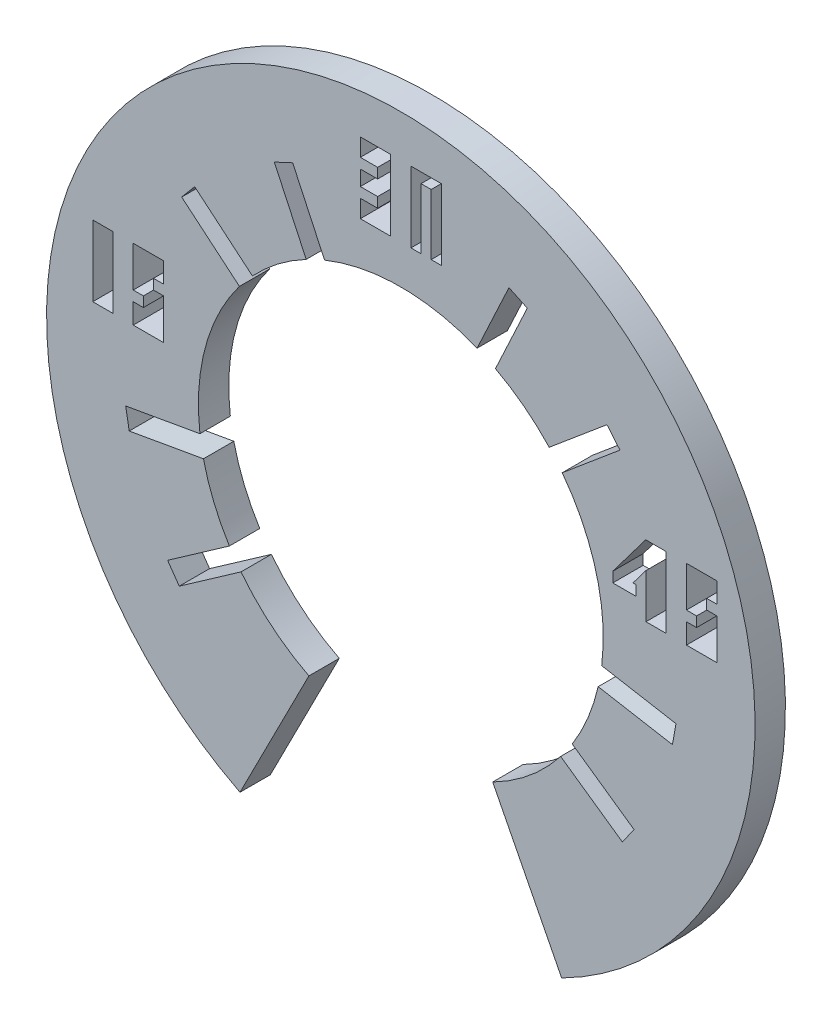
SolidWorks part; units mm, degrees
ref_plane "Спереди" through (0, 0, 0) normal (0, 0, 1) x (1, 0, 0)
ref_plane "Сверху" through (0, 0, 0) normal (0, 1, 0) x (1, 0, 0)
ref_plane "Справа" through (0, 0, 0) normal (1, 0, 0) x (0, 0, -1)
sketch "Sketch1" plane through (0, 0, 0) normal (0, 0, 1) x (1, 0, 0)
  line L1 (-4.5399, -8.9101) -> (-7.9448, -15.5926)
  line L2 (4.5399, -8.9101) -> (7.9448, -15.5926)
  arc A0 (4.5399, -8.9101) -> (-4.5399, -8.9101) centre (0, 0) ccw
  arc A1 (7.9448, -15.5926) -> (-7.9448, -15.5926) centre (0, 0) ccw
  point P34 (0, 0)
  dimension "D1" = 20
  dimension "D2" = 35
extrude "Boss-Extrude1" add sketch "Sketch1" along normal blind 1.5
sketch "Sketch2" plane through (0, 0, 1.5) normal (0, 0, 1) x (1, 0, 0)
  line L0 (0, 0) -> (0, -15.8219) construction
  line L1 (0, 0) -> (-8.75, -15.1554) construction
  line L2 (0, 0) -> (-14.3352, -10.0376) construction
  line L3 (0, 0) -> (-17.2341, -3.0388) construction
  line L4 (0, 0) -> (-16.9037, 4.5293) construction
  line L5 (0, 0) -> (-13.4058, 11.2488) construction
  line L6 (0, 0) -> (-7.3958, 15.8604) construction
  line L7 (0, 0) -> (0, 17.5) construction
  line L8 (0, 0) -> (7.3958, 15.8604) construction
  line L9 (0, 0) -> (13.4058, 11.2488) construction
  line L10 (0, 0) -> (16.9037, 4.5293) construction
  line L11 (0, 0) -> (17.2341, -3.0388) construction
  line L12 (0, 0) -> (14.3352, -10.0376) construction
  line L13 (0, 0) -> (8.75, -15.1554) construction
  line L14 (-15.218, 5.2576) -> (-14.218, 5.2576)
  line L15 (-14.218, 5.2576) -> (-14.218, 1.7576)
  line L16 (-14.218, 1.7576) -> (-15.218, 1.7576)
  line L17 (-15.218, 1.7576) -> (-15.218, 5.2576)
  line L18 (-13.218, 5.2576) -> (-13.218, 3.2576)
  line L19 (-13.218, 3.2576) -> (-12.718, 3.2576)
  line L20 (-12.718, 3.2576) -> (-12.718, 2.7576)
  line L21 (-12.718, 2.7576) -> (-13.218, 2.7576)
  line L22 (-13.218, 2.7576) -> (-13.218, 1.7576)
  line L23 (-13.218, 1.7576) -> (-11.718, 1.7576)
  line L24 (-11.718, 1.7576) -> (-11.718, 3.7576)
  line L25 (-11.718, 3.7576) -> (-12.218, 3.7576)
  line L26 (-12.218, 3.7576) -> (-12.218, 4.2576)
  line L27 (-12.218, 4.2576) -> (-11.718, 4.2576)
  line L28 (-11.718, 4.2576) -> (-11.718, 5.2576)
  line L29 (-11.718, 5.2576) -> (-13.218, 5.2576)
  line L30 (-2, 15.4185) -> (-0.5, 15.4185)
  line L31 (-0.5, 15.4185) -> (-0.5, 11.9185)
  line L32 (-0.5, 11.9185) -> (-2, 11.9185)
  line L33 (-2, 11.9185) -> (-2, 12.7935)
  line L34 (-2, 12.7935) -> (-1.1453, 12.7935)
  line L35 (-1.1453, 12.7935) -> (-1.1453, 13.2935)
  line L36 (-1.1453, 13.2935) -> (-2, 13.2935)
  line L37 (-2, 13.2935) -> (-2, 14.0435)
  line L38 (-2, 14.0435) -> (-1.1453, 14.0435)
  line L39 (-1.1453, 14.0435) -> (-1.1453, 14.5435)
  line L40 (-1.1453, 14.5435) -> (-2, 14.5435)
  line L41 (-2, 14.5435) -> (-2, 15.4185)
  line L42 (0.5, 15.4185) -> (0.5, 11.9185)
  line L43 (0.5, 11.9185) -> (1, 11.9185)
  line L44 (2, 11.9185) -> (2, 15.4185)
  line L45 (2, 15.4185) -> (0.5, 15.4185)
  line L46 (1, 14.9185) -> (1.5, 14.9185)
  line L47 (1.5, 14.9185) -> (1.5, 12.4185)
  line L48 (1.5, 11.9185) -> (2, 11.9185)
  line L49 (1, 12.4185) -> (1, 14.9185)
  line L50 (1, 12.4185) -> (1, 11.9185)
  line L51 (1.5, 12.4185) -> (1.5, 11.9185)
  line L52 (12.0977, 5.2314) -> (13.1104, 5.2314)
  line L53 (13.1104, 5.2314) -> (13.1104, 1.7314)
  line L54 (13.1104, 1.7314) -> (12.1104, 1.7314)
  line L55 (12.1104, 1.7314) -> (12.1104, 3.9221)
  line L56 (14.1104, 5.2314) -> (14.1104, 3.2314)
  line L57 (14.1104, 3.2314) -> (14.6104, 3.2314)
  line L58 (14.6104, 3.2314) -> (14.6104, 2.7314)
  line L59 (14.6104, 2.7314) -> (14.1104, 2.7314)
  line L60 (14.1104, 2.7314) -> (14.1104, 1.7314)
  line L61 (14.1104, 1.7314) -> (15.6104, 1.7314)
  line L62 (15.6104, 1.7314) -> (15.6104, 3.7314)
  line L63 (15.6104, 3.7314) -> (15.1104, 3.7314)
  line L64 (15.1104, 3.7314) -> (15.1104, 4.2314)
  line L65 (15.1104, 4.2314) -> (15.6104, 4.2314)
  line L66 (15.6104, 4.2314) -> (15.6104, 5.2314)
  line L67 (15.6104, 5.2314) -> (14.1104, 5.2314)
  line L68 (12.0977, 5.2314) -> (10.4706, 3.0735)
  line L69 (-11.2326, -7.8651) -> (-11.5194, -7.4556)
  line L70 (11.4706, 3.0735) -> (12.1104, 3.9221)
  line L71 (10.4706, 3.0735) -> (10.4706, 2.5723)
  line L72 (10.4706, 2.5723) -> (11.6104, 2.5723)
  line L73 (11.6104, 2.5723) -> (11.6104, 3.0735)
  line L74 (11.6104, 3.0735) -> (11.4706, 3.0735)
  line L75 (-11.5194, -7.4556) -> (-8.4681, -5.319)
  line L76 (-11.2326, -7.8651) -> (-10.9458, -8.2747)
  line L77 (-10.9458, -8.2747) -> (-7.8945, -6.1382)
  line L78 (-8.4681, -5.319) -> (-7.4734, -4.6225)
  line L79 (-7.4734, -4.6225) -> (-6.8998, -5.4417)
  line L80 (-6.8998, -5.4417) -> (-7.8945, -6.1382)
  line L81 (-13.5041, -2.3811) -> (-13.5909, -1.8887)
  line L82 (-13.5909, -1.8887) -> (-9.9226, -1.2419)
  line L83 (-13.5041, -2.3811) -> (-13.4173, -2.8735)
  line L84 (-13.4173, -2.8735) -> (-9.7489, -2.2267)
  line L85 (-9.9226, -1.2419) -> (-8.7268, -1.0311)
  line L86 (-8.7268, -1.0311) -> (-8.5531, -2.0159)
  line L87 (-8.5531, -2.0159) -> (-9.7489, -2.2267)
  line L95 (-10.5043, 8.8142) -> (-10.1829, 9.1972)
  line L96 (-10.1829, 9.1972) -> (-7.3295, 6.8029)
  line L97 (-10.5043, 8.8142) -> (-10.8257, 8.4312)
  line L98 (-10.8257, 8.4312) -> (-7.9723, 6.0368)
  line L99 (-7.3295, 6.8029) -> (-6.3993, 6.0223)
  line L100 (-6.3993, 6.0223) -> (-7.0421, 5.2563)
  line L101 (-7.0421, 5.2563) -> (-7.9723, 6.0368)
  line L102 (-5.7951, 12.4277) -> (-5.342, 12.639)
  line L103 (-5.342, 12.639) -> (-3.7677, 9.2631)
  line L104 (-5.7951, 12.4277) -> (-6.2483, 12.2164)
  line L105 (-6.2483, 12.2164) -> (-4.6741, 8.8404)
  line L106 (-3.7677, 9.2631) -> (-3.2546, 8.1626)
  line L107 (-3.2546, 8.1626) -> (-4.1609, 7.7399)
  line L108 (-4.1609, 7.7399) -> (-4.6741, 8.8404)
  line L116 (5.7951, 12.4277) -> (6.2483, 12.2164)
  line L117 (6.2483, 12.2164) -> (4.6741, 8.8404)
  line L118 (5.7951, 12.4277) -> (5.342, 12.639)
  line L119 (5.342, 12.639) -> (3.7677, 9.2631)
  line L120 (4.6741, 8.8404) -> (4.1609, 7.7399)
  line L121 (4.1609, 7.7399) -> (3.2546, 8.1626)
  line L122 (3.2546, 8.1626) -> (3.7677, 9.2631)
  line L123 (10.5043, 8.8142) -> (10.8257, 8.4312)
  line L124 (10.8257, 8.4312) -> (7.9723, 6.0368)
  line L125 (10.5043, 8.8142) -> (10.1829, 9.1972)
  line L126 (10.1829, 9.1972) -> (7.3295, 6.8029)
  line L127 (7.9723, 6.0368) -> (7.0421, 5.2563)
  line L128 (7.0421, 5.2563) -> (6.3993, 6.0223)
  line L129 (6.3993, 6.0223) -> (7.3295, 6.8029)
  line L137 (13.5041, -2.3811) -> (13.4173, -2.8735)
  line L138 (13.4173, -2.8735) -> (9.7489, -2.2267)
  line L139 (13.5041, -2.3811) -> (13.5909, -1.8887)
  line L140 (13.5909, -1.8887) -> (9.9226, -1.2419)
  line L141 (9.7489, -2.2267) -> (8.5531, -2.0159)
  line L142 (8.5531, -2.0159) -> (8.7268, -1.0311)
  line L143 (8.7268, -1.0311) -> (9.9226, -1.2419)
  line L144 (11.2326, -7.8651) -> (10.9458, -8.2747)
  line L145 (10.9458, -8.2747) -> (7.8945, -6.1382)
  line L146 (11.2326, -7.8651) -> (11.5194, -7.4556)
  line L147 (11.5194, -7.4556) -> (8.4681, -5.319)
  line L148 (7.8945, -6.1382) -> (6.8998, -5.4417)
  line L149 (6.8998, -5.4417) -> (7.4734, -4.6225)
  line L150 (7.4734, -4.6225) -> (8.4681, -5.319)
  line L165 (0, 13.7124) -> (0.5, 13.7124) [skipped]
  line L166 (0, 13.7124) -> (-0.5, 13.7124) [skipped]
  line L167 (-0.5, 13.7124) -> (-0.5, 9.9875) [skipped]
  line L168 (0.5, 13.7124) -> (0.5, 9.9875) [skipped]
  line L169 (0.5, 9.9875) -> (0.5, 8.7732) [skipped]
  line L170 (0.5, 8.7732) -> (-0.5, 8.7732) [skipped]
  line L171 (-0.5, 8.7732) -> (-0.5, 9.9875) [skipped]
  line L172 (-13.1158, 4.032) -> (-9.5178, 3.0679) [skipped]
  line L173 (-13.2452, 3.549) -> (-13.1158, 4.032) [skipped]
  line L174 (-13.2452, 3.549) -> (-13.3746, 3.0661) [skipped]
  line L175 (-13.3746, 3.0661) -> (-9.7766, 2.102) [skipped]
  line L176 (-8.6037, 1.7877) -> (-9.7766, 2.102) [skipped]
  line L177 (-9.5178, 3.0679) -> (-8.3449, 2.7536) [skipped]
  line L178 (-8.3449, 2.7536) -> (-8.6037, 1.7877) [skipped]
  line L179 (1.1951, -13.6603) -> (0.697, -13.7038) [skipped]
  line L180 (0.697, -13.7038) -> (0.3724, -9.9931) [skipped]
  line L181 (1.1951, -13.6603) -> (1.6932, -13.6167) [skipped]
  line L182 (1.6932, -13.6167) -> (1.3686, -9.9059) [skipped]
  line L183 (0.3724, -9.9931) -> (0.2665, -8.7834) [skipped]
  line L184 (0.2665, -8.7834) -> (1.2627, -8.6963) [skipped]
  line L185 (1.2627, -8.6963) -> (1.3686, -9.9059) [skipped]
  line L186 (13.1158, 4.032) -> (9.5178, 3.0679) [skipped]
  line L187 (13.3746, 3.0661) -> (9.7766, 2.102) [skipped]
  line L188 (13.2452, 3.549) -> (13.1158, 4.032) [skipped]
  line L189 (13.2452, 3.549) -> (13.3746, 3.0661) [skipped]
  line L190 (8.3449, 2.7536) -> (9.5178, 3.0679) [skipped]
  line L191 (9.7766, 2.102) -> (8.6037, 1.7877) [skipped]
  line L192 (8.6037, 1.7877) -> (8.3449, 2.7536) [skipped]
  line L193 (4.5607, -8.8994) -> (3.9536, -7.8478) [skipped]
  line L194 (3.9536, -7.8478) -> (4.8196, -7.3478) [skipped]
  line L195 (4.8196, -7.3478) -> (5.4268, -8.3994) [skipped]
  line L196 (7.2892, -11.6253) -> (5.4268, -8.3994) [skipped]
  line L197 (6.8562, -11.8753) -> (6.4232, -12.1253) [skipped]
  line L198 (6.8562, -11.8753) -> (7.2892, -11.6253) [skipped]
  line L199 (6.4232, -12.1253) -> (4.5607, -8.8994) [skipped]
  arc A0 (7.9448, -15.5926) -> (-7.9448, -15.5926) centre (0, 0) ccw construction
  arc A1 (4.5399, -8.9101) -> (-4.5399, -8.9101) centre (0, 0) ccw construction
  point P22 (0, 0)
  point P177 (0, 0)
  dimension "D1" = 30
  dimension "D2" = 3.5
  dimension "D3" = 1
  dimension "D4" = 1
  dimension "D5" = 0.5
  dimension "D6" = 0.5
  dimension "D7" = 2
  dimension "D8" = 1
  dimension "D9" = 1.5
  dimension "D10" = 1.5
  dimension "D11" = 1
  dimension "D12" = 1
  dimension "D14" = 3.5
  dimension "D15" = 0.5
  dimension "D16" = 0.5
  dimension "D17" = 1.5
  dimension "D18" = 0.5
  dimension "D19" = 0.75
  dimension "D20" = 0.875
  dimension "D21" = 1.5
  dimension "D22" = 3.5
  dimension "D23" = 0.5
  dimension "D24" = 0.5
  dimension "D25" = 0.5
  dimension "D26" = 0.5
  dimension "D27" = 3.5
  dimension "D28" = 1
  dimension "D29" = 1
  dimension "D30" = 0.5
  dimension "D31" = 0.5
  dimension "D32" = 2
  dimension "D33" = 1
  dimension "D34" = 1.5
  dimension "D35" = 1
  dimension "D36" = 1.5
  dimension "D37" = 1
  dimension "D38" = 1
  dimension "D39" = 0.5
  dimension "D40" = 0.5
  dimension "D41" = 0.5
  dimension "D13" = 13
  dimension "D42" = 13
extrude "Cut-Extrude1" cut sketch "Sketch2" against normal blind 1.5
